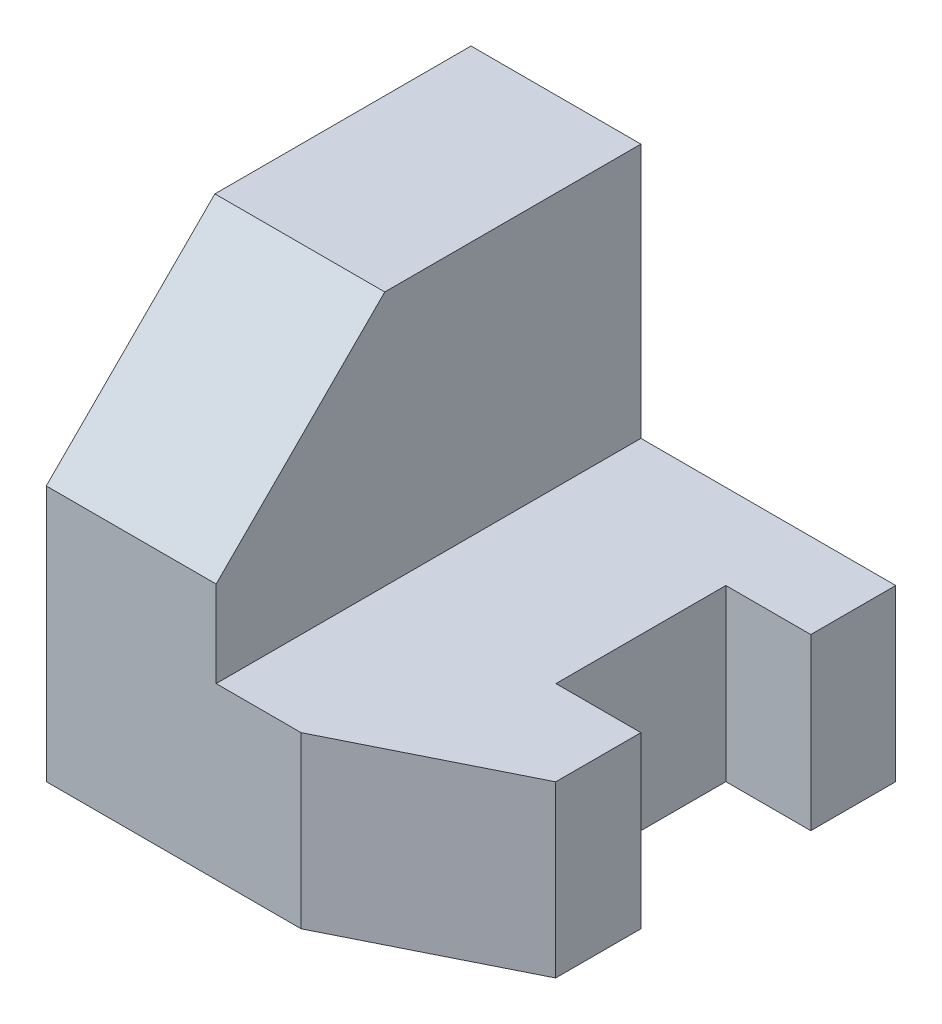
SolidWorks part; units mm, degrees
ref_plane "Front Plane" through (0, 0, 0) normal (0, 0, 1) x (1, 0, 0)
ref_plane "Top Plane" through (0, 0, 0) normal (0, 1, 0) x (1, 0, 0)
ref_plane "Right Plane" through (0, 0, 0) normal (1, 0, 0) x (0, 0, -1)
sketch "Sketch1" plane through (0, 0, 0) normal (0, 1, 0) x (1, 0, 0)
  line L1 (-25, -25) -> (25, -25)
  line L2 (-25, -25) -> (-25, 25)
  line L3 (-25, 25) -> (25, 25)
  line L4 (25, -25) -> (25, 25)
  line L5 (-25, -25) -> (25, 25) construction
  line L6 (-25, 25) -> (25, -25) construction
  point P0 (0, 0)
  dimension "D1" = 50
  dimension "D2" = 50
extrude "Boss-Extrude1" add sketch "Sketch1" along normal blind 50
sketch "Sketch3" plane through (0, 0, 25) normal (0, 0, 1) x (1, 0, 0)
  line L0 (-5, 55.2462) -> (-5, -11.7608) construction
  line L1 (-38.1584, 20) -> (31.1473, 20) construction
  line L2 (-5, 50) -> (-5, 20)
  line L3 (-5, 20) -> (25.0558, 20)
  line L4 (25.0558, 20) -> (25, 50)
  line L5 (25, 50) -> (-5, 50)
  dimension "D1" = 20
  dimension "D2" = 20
  dimension "D3" = 25.0558
  dimension "D4" = 20
  dimension "D5" = 30
extrude "Cut-Extrude2" cut sketch "Sketch3" against normal through all
sketch "Sketch4" plane through (25, 0, 0) normal (1, 0, 0) x (0, 0, -1)
  line L0 (15, 53.4599) -> (15, -15.2833) construction
  line L1 (-25, 0) -> (25, 0) construction
  line L2 (15, 0) -> (-5, 0)
  line L3 (15, 0) -> (15, 20)
  line L4 (15, 20) -> (-5, 20)
  line L5 (-5, 0) -> (-5, 20)
  dimension "D1" = 10
  dimension "D2" = 20
  dimension "D3" = 20
extrude "Cut-Extrude3" cut sketch "Sketch4" against normal blind 10
sketch "Sketch7" plane through (0, 0, 25) normal (0, 0, 1) x (1, 0, 0)
  line L0 (-1.1954, 30) -> (-40.1833, 30) construction
  dimension "D1" = 30
sketch "Sketch8" plane through (-5, 0, 0) normal (1, 0, 0) x (0, 0, -1)
  line L0 (-5, 53.7835) -> (-5, -3.2421) construction
  line L1 (-37.5259, 30) -> (28.7342, 30) construction
  line L2 (-25.1497, 30) -> (-5, 50.1497)
  dimension "D1" = 20
  dimension "D2" = 30
  dimension "D3" = 25.1497
  dimension "D4" = 50.1497
extrude "Cut-Extrude4" cut sketch "Sketch8" against normal through all and the other way through all
sketch "Sketch9" plane through (0, 20, 0) normal (0, 1, 0) x (1, 0, 0)
  line L0 (5, 30.0809) -> (5, -31.2375) construction
  line L1 (25.0591, -15) -> (5, -25)
  line L2 (-5, -25) -> (25, -25) construction
  line L3 (27.1919, -15) -> (-34.4464, -15) construction
  dimension "D1" = 10
  dimension "D2" = 10
  dimension "D3" = 29.2054
extrude "Cut-Extrude5" cut sketch "Sketch9" against normal through all and the other way through all
